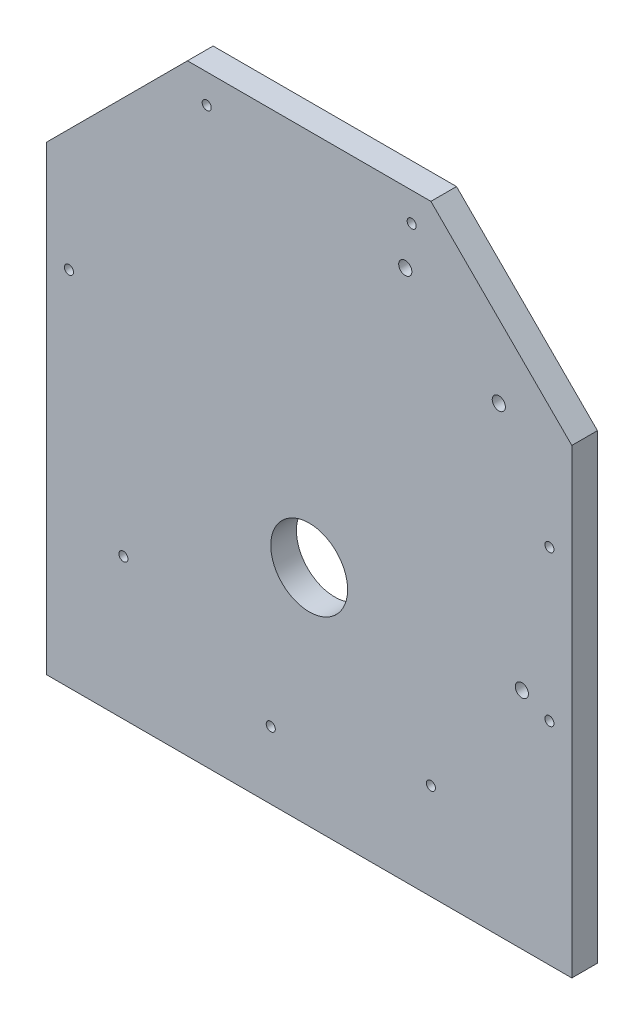
SolidWorks part; units mm, degrees
ref_plane "Front Plane" through (0, 0, 0) normal (0, 0, 1) x (1, 0, 0)
ref_plane "Top Plane" through (0, 0, 0) normal (0, 1, 0) x (1, 0, 0)
ref_plane "Right Plane" through (0, 0, 0) normal (1, 0, 0) x (0, 0, -1)
sketch "Sketch1" plane through (0, 0, 0) normal (0, 0, 1) x (1, 0, 0)
  line L0 (-130.175, -168.275) -> (130.175, -168.275)
  line L1 (130.175, -168.275) -> (130.175, 60.325)
  line L2 (130.175, 60.325) -> (60.325, 130.175)
  line L3 (60.325, 130.175) -> (-60.325, 130.175)
  line L4 (-60.325, 130.175) -> (-130.175, 60.325)
  line L5 (-130.175, 60.325) -> (-130.175, -168.275)
  point P0 (0, -168.275)
  point P2 (0, 130.175)
  dimension "D1" = 260.35
  dimension "D2" = 298.45
  dimension "D3" = 130.175
  dimension "D4" = 69.85
  dimension "D5" = 45
extrude "Boss-Extrude1" add sketch "Sketch1" along normal blind 12.7
sketch "Sketch2" plane through (0, 0, 0) normal (0, 0, 1) x (1, 0, 0)
  circle A0 centre (0, -57.15) radius 19.05
  dimension "D1" = 38.1
  dimension "D2" = 57.15
extrude "Cut-Extrude1" cut sketch "Sketch2" along normal through all
hole_wizard "#16 (0.177) Diameter Hole1" positions "Sketch4" profile "Sketch3" hole size "#16" standard "ANSI Inch" end condition through all
sketch "Sketch4" plane through (0, 0, 12.7) normal (0, 0, 1) x (1, 0, 0)
  point P0 (-50.8, 115.9002)
  point P2 (50.8, 115.9002)
  point P4 (119.0752, 11.1252)
  point P6 (119.0752, -63.5)
  point P8 (60.325, -120.65)
  point P10 (-19.05, -134.9375)
  point P12 (-92.075, -98.425)
  point P14 (-119.0752, 11.1252)
  dimension "D1" = 115.9002
  dimension "D2" = 50.8
  dimension "D3" = 50.8
  dimension "D4" = 11.1252
  dimension "D5" = 119.0752
  dimension "D6" = 119.0752
  dimension "D7" = 98.425
  dimension "D8" = 63.5
  dimension "D9" = 92.075
  dimension "D10" = 120.65
  dimension "D11" = 60.325
  dimension "D12" = 134.9375
  dimension "D13" = 19.05
sketch "Sketch3" plane through (-50.8, 115.9002, 12.7) normal (1, 0, 0) x (0, -1, 0)
  line L0 (0, 0) -> (0, 12.7)
  line L1 (0, 12.7) -> (2.2479, 12.7)
  line L2 (2.2479, 12.7) -> (2.2479, 0)
  line L5 (2.2479, 0) -> (0, 0)
  line L11 (0, -6.35) -> (0, 107.95) construction
  dimension "Thru Hole Dia." = 4.4958
  dimension "Thru Hole Depth" = 12.7
hole_wizard "F (0.257) Diameter Hole1" positions "Sketch6" profile "Sketch5" hole size "F" standard "ANSI Inch" end condition through all
sketch "Sketch6" plane through (0, 0, 0) normal (0, 0, -1) x (-1, 0, 0)
  point P0 (-105.41, -57.15)
  point P2 (-93.98, 60.325)
  point P4 (-47.625, 95.25)
  point P12 (-98.5257, -45.793)
  point P17 (-105.41, -44.3005)
  dimension "D1" = 105.41
  dimension "D2" = 57.15
  dimension "D3" = 93.98
  dimension "D4" = 60.325
  dimension "D5" = 47.625
  dimension "D6" = 95.25
sketch "Sketch5" plane through (105.41, -57.15, 0) normal (1, 0, 0) x (0, 1, 0)
  line L0 (0, 0) -> (0, 12.7)
  line L1 (0, 12.7) -> (3.2639, 12.7)
  line L2 (3.2639, 12.7) -> (3.2639, 0)
  line L5 (3.2639, 0) -> (0, 0)
  line L11 (0, -6.35) -> (0, 107.95) construction
  dimension "Thru Hole Dia." = 6.5278
  dimension "Thru Hole Depth" = 12.7
